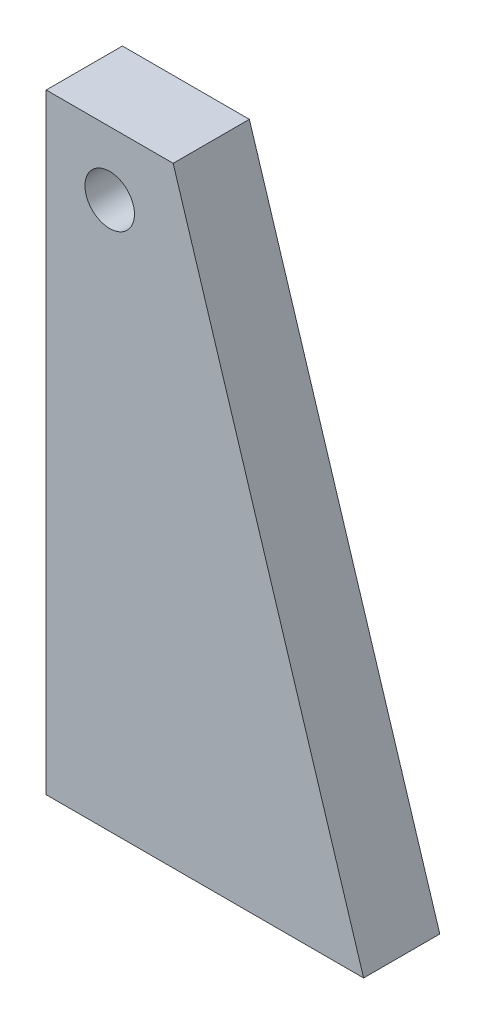
SolidWorks part; units mm, degrees
ref_plane "前视基准面" through (0, 0, 0) normal (0, 0, 1) x (1, 0, 0)
ref_plane "上视基准面" through (0, 0, 0) normal (0, 1, 0) x (1, 0, 0)
ref_plane "右视基准面" through (0, 0, 0) normal (1, 0, 0) x (0, 0, -1)
sketch "草图1" plane through (0, 0, 0) normal (0, 0, 1) x (1, 0, 0)
  line L0 (0, -55) -> (0, 55) construction
  line L2 (0, 0) -> (-5, 0)
  line L3 (55, 0) -> (-55, 0) construction
  line L4 (0, 0) -> (20, 0)
  line L5 (-5, 0) -> (-5, 48.07)
  line L6 (-5, 48.07) -> (5, 48.07)
  line L7 (5, 48.07) -> (20, 0)
  circle A0 centre (0, 43.07) radius 1.95
extrude "凸台-拉伸1" add sketch "草图1" along normal blind 6
